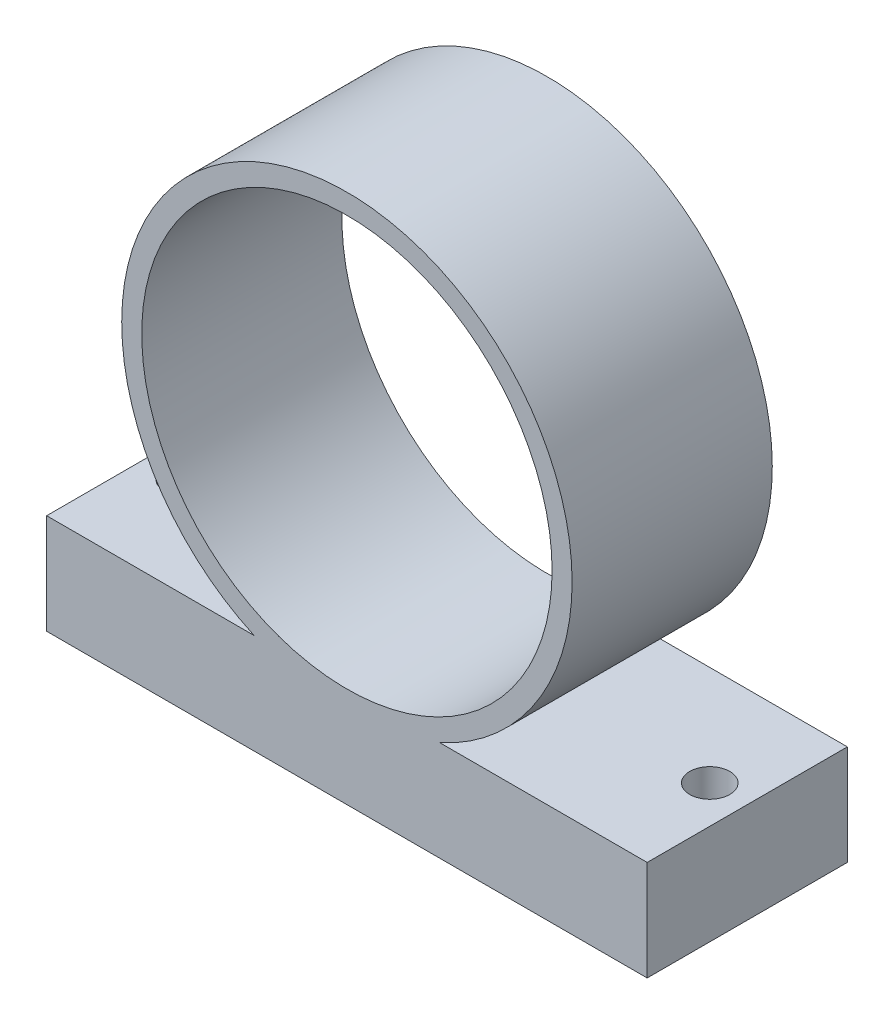
SolidWorks part; units mm, degrees
ref_plane "Front Plane" through (0, 0, 0) normal (0, 0, 1) x (1, 0, 0)
ref_plane "Top Plane" through (0, 0, 0) normal (0, 1, 0) x (1, 0, 0)
ref_plane "Right Plane" through (0, 0, 0) normal (1, 0, 0) x (0, 0, -1)
sketch "Sketch1" plane through (0, 0, 0) normal (0, 0, 1) x (1, 0, 0)
  circle A0 centre (0, 0) radius 22.5
  circle A1 centre (0, 0) radius 20.5
  dimension "D1" = 45
  dimension "D2" = 41
extrude "Boss-Extrude2" add sketch "Sketch1" along normal blind 20
sketch "Sketch2" plane through (0, 0, 0) normal (0, 0, -1) x (-1, 0, 0)
  line L0 (-30, -20.5) -> (30, -20.5)
  line L1 (30, -20.5) -> (30, -30.5)
  line L2 (30, -30.5) -> (-30, -30.5)
  line L3 (-30, -30.5) -> (-30, -20.5)
  dimension "D3" = 10
  dimension "D4" = 10
  dimension "D6" = 60
extrude "Boss-Extrude3" add sketch "Sketch2" against normal blind 20 contours L3 L0 L1 L2
sketch "Sketch3" plane through (0, -20.5, 0) normal (0, 1, 0) x (1, 0, 0)
  line L0 (30, 0) -> (9.2736, 0) construction
  line L1 (-9.2736, 0) -> (-30, 0) construction
  line L2 (-30, -20) -> (-30, 0) construction
  line L3 (30, -20) -> (30, 0) construction
  circle A0 centre (26.25, -10) radius 2
  circle A1 centre (-26.25, -10) radius 2
  dimension "D1" = 4
  dimension "D2" = 4
  dimension "D3" = 10
  dimension "D4" = 10
  dimension "D5" = 3.75
  dimension "D6" = 3.75
extrude "Cut-Extrude1" cut sketch "Sketch3" against normal blind 20
